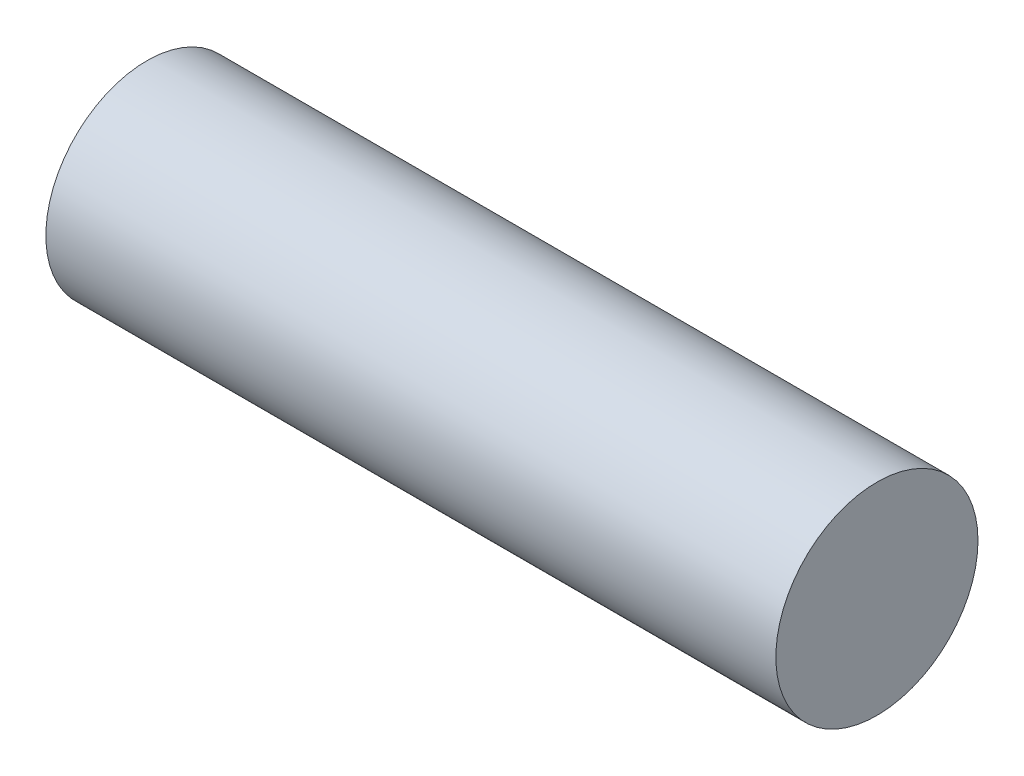
SolidWorks part; units mm, degrees
ref_plane "Front Plane" through (0, 0, 0) normal (0, 0, 1) x (1, 0, 0)
ref_plane "Top Plane" through (0, 0, 0) normal (0, 1, 0) x (1, 0, 0)
ref_plane "Right Plane" through (0, 0, 0) normal (1, 0, 0) x (0, 0, -1)
sketch "Sketch1" plane through (0, 0, 0) normal (1, 0, 0) x (0, 0, -1)
  circle A0 centre (0, 0) radius 9
  dimension "D1" = 18
extrude "Boss-Extrude1" add sketch "Sketch1" along normal blind 65
